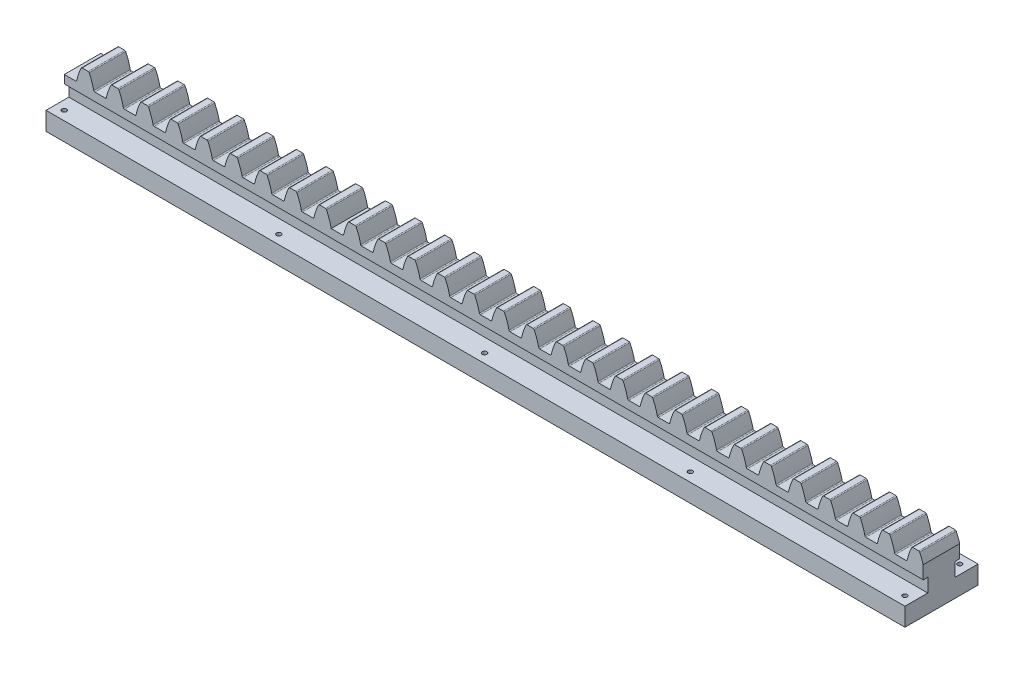
SolidWorks part; units mm, degrees
ref_plane "Front Plane" through (0, 0, 0) normal (0, 0, 1) x (1, 0, 0)
ref_plane "Top Plane" through (0, 0, 0) normal (0, 1, 0) x (1, 0, 0)
ref_plane "Right Plane" through (0, 0, 0) normal (1, 0, 0) x (0, 0, -1)
sketch "Sketch1" plane through (0, 0, 0) normal (1, 0, 0) x (0, 0, -1)
  line L0 (0, 0) -> (0, 103.7315) construction
  line L1 (25.4, 0) -> (-25.4, 0)
  line L2 (-25.4, 0) -> (-25.4, 12.7)
  line L3 (25.4, 0) -> (25.4, 12.7)
  line L4 (-25.4, 12.7) -> (-9.525, 12.7)
  line L5 (-9.525, 12.7) -> (-9.525, 22.225)
  line L6 (9.525, 12.7) -> (9.525, 22.225)
  line L7 (-9.525, 22.225) -> (-12.7, 22.225)
  line L8 (9.525, 22.225) -> (12.7, 22.225)
  line L9 (-12.7, 22.225) -> (-12.7, 38.1)
  line L10 (12.7, 22.225) -> (12.7, 38.1)
  line L11 (-12.7, 38.1) -> (12.7, 38.1)
  line L12 (9.525, 12.7) -> (25.4, 12.7)
  point P7 (0, 25.4)
  point P16 (0, 38.1)
  dimension "D1" = 9.525
  dimension "D2" = 12.7
  dimension "D3" = 38.1
  dimension "D4" = 50.8
  dimension "D5" = 19.05
  dimension "D6" = 25.4
extrude "Boss-Extrude2" add sketch "Sketch1" along normal mid plane 597.281
sketch "Sketch6" plane through (23.4746, 68.7839, 0) normal (0, 0, -1) x (1, 0, 0)
  line L3 (-322.1151, 30.6839) -> (-322.1151, 46.5589) construction
  line L4 (-317.8651, 30.6839) -> (-317.8651, 40.8439) construction
  line L5 (-313.6151, 40.8439) -> (-322.1151, 40.8439) construction
  line L6 (-322.1151, 40.8439) -> (-313.6151, 40.8439)
  line L7 (-325.6151, 30.6839) -> (-310.1151, 30.6839)
  line L8 (275.1659, 30.6839) -> (-322.1151, 30.6839) construction
  arc A0 (-313.6151, 40.8439) -> (-310.1151, 30.6839) centre (-273.7784, 48.8843) ccw
  arc A9 (-325.6151, 30.6839) -> (-322.1151, 40.8439) centre (-361.9518, 48.8843) ccw
  dimension "D1" = 10.16
  dimension "D2" = 8.5
  dimension "D4" = 40.64
  dimension "D5" = 15.5
extrude "Cut-Extrude4" cut sketch "Sketch6" against normal through all and the other way through all
pattern_linear "LPattern1" count 30 spacing 20.6248 along (1, 0, 0) of "Cut-Extrude4"
fillet "Fillet1" radius 0.762 114 edges at (270.2291, 38.1, 0) (275.3539, 38.1, 0) (290.8539, 38.1, 0) (295.9787, 38.1, 0) (287.3539, 27.94, 0) (278.8539, 27.94, 0) (266.7291, 27.94, 0) (258.2291, 27.94, 0) (254.7291, 38.1, 0) (249.6043, 38.1, 0) (234.1043, 38.1, 0) (228.9795, 38.1, 0) (213.4795, 38.1, 0) (208.3547, 38.1, 0) (192.8547, 38.1, 0) (187.7299, 38.1, 0) (172.2299, 38.1, 0) (167.1051, 38.1, 0) (151.6051, 38.1, 0) (146.4803, 38.1, 0) (246.1043, 27.94, 0) (237.6043, 27.94, 0) (225.4795, 27.94, 0) (216.9795, 27.94, 0) (204.8547, 27.94, 0) (196.3547, 27.94, 0) (184.2299, 27.94, 0) (175.7299, 27.94, 0) (163.6051, 27.94, 0) (155.1051, 27.94, 0) (142.9803, 27.94, 0) (134.4803, 27.94, 0) (130.9803, 38.1, 0) (125.8555, 38.1, 0) (122.3555, 27.94, 0) (113.8555, 27.94, 0) (110.3555, 38.1, 0) (105.2307, 38.1, 0) (101.7307, 27.94, 0) (93.2307, 27.94, 0) (89.7307, 38.1, 0) (84.6059, 38.1, 0) (81.1059, 27.94, 0) (72.6059, 27.94, 0) (69.1059, 38.1, 0) (63.9811, 38.1, 0) (60.4811, 27.94, 0) (51.9811, 27.94, 0) (48.4811, 38.1, 0) (43.3563, 38.1, 0) (39.8563, 27.94, 0) (27.8563, 38.1, 0) (22.7315, 38.1, 0) (7.2315, 38.1, 0) (2.1067, 38.1, 0) (-13.3933, 38.1, 0) (-18.5181, 38.1, 0) (31.3563, 27.94, 0) (19.2315, 27.94, 0) (10.7315, 27.94, 0) (-1.3933, 27.94, 0) (-9.8933, 27.94, 0) (-22.0181, 27.94, 0) (-30.5181, 27.94, 0) (-34.0181, 38.1, 0) (-39.1429, 38.1, 0) (-42.6429, 27.94, 0) (-51.1429, 27.94, 0) (-63.2677, 27.94, 0) (-71.7677, 27.94, 0) (-83.8925, 27.94, 0) (-92.3925, 27.94, 0) (-104.5173, 27.94, 0) (-54.6429, 38.1, 0) (-59.7677, 38.1, 0) (-75.2677, 38.1, 0) (-80.3925, 38.1, 0) (-95.8925, 38.1, 0) (-101.0173, 38.1, 0) (-116.5173, 38.1, 0) (-121.6421, 38.1, 0) (-125.1421, 27.94, 0) (-133.6421, 27.94, 0) (-137.1421, 38.1, 0) (-142.2669, 38.1, 0) (-157.7669, 38.1, 0) (-162.8917, 38.1, 0) (-178.3917, 38.1, 0) (-183.5165, 38.1, 0) (-145.7669, 27.94, 0) (-154.2669, 27.94, 0) (-166.3917, 27.94, 0) (-174.8917, 27.94, 0) (-187.0165, 27.94, 0) (-195.5165, 27.94, 0) (-199.0165, 38.1, 0) (-204.1413, 38.1, 0) (-207.6413, 27.94, 0) (-216.1413, 27.94, 0) (-219.6413, 38.1, 0) (-224.7661, 38.1, 0) (-228.2661, 27.94, 0) (-236.7661, 27.94, 0) (-240.2661, 38.1, 0) (-245.3909, 38.1, 0) (-248.8909, 27.94, 0) (-257.3909, 27.94, 0) (-260.8909, 38.1, 0) (-266.0157, 38.1, 0) (-278.0157, 27.94, 0) (-269.5157, 27.94, 0) (-290.1405, 27.94, 0) (-281.5157, 38.1, 0) (-286.6405, 38.1, 0)
sketch "Sketch4" plane through (0, 12.7, 0) normal (0, 1, 0) x (1, 0, 0)
  line L0 (0, 0) -> (0, 69.1795) construction
  line L1 (0, 0) -> (-248.0623, 0) construction
  line L2 (-298.6405, 25.4) -> (-298.6405, 9.525) construction
  line L3 (298.6405, 25.4) -> (-298.6405, 25.4) construction
  circle A0 centre (-292.2905, 19.05) radius 1.5875
  circle A1 centre (-292.2905, -19.05) radius 1.5875
  circle A2 centre (-143.0655, 19.05) radius 1.5875
  circle A3 centre (-143.0655, -19.05) radius 1.5875
  circle A4 centre (0, 19.05) radius 1.5875
  circle A5 centre (0, -19.05) radius 1.5875
  circle A6 centre (143.0655, -19.05) radius 1.5875
  circle A7 centre (143.0655, 19.05) radius 1.5875
  circle A8 centre (292.2905, -19.05) radius 1.5875
  circle A9 centre (292.2905, 19.05) radius 1.5875
  dimension "D1" = 3.175
  dimension "D2" = 6.35
  dimension "D3" = 6.35
  dimension "D4" = 149.225
extrude "Cut-Extrude2" cut sketch "Sketch4" against normal through all
